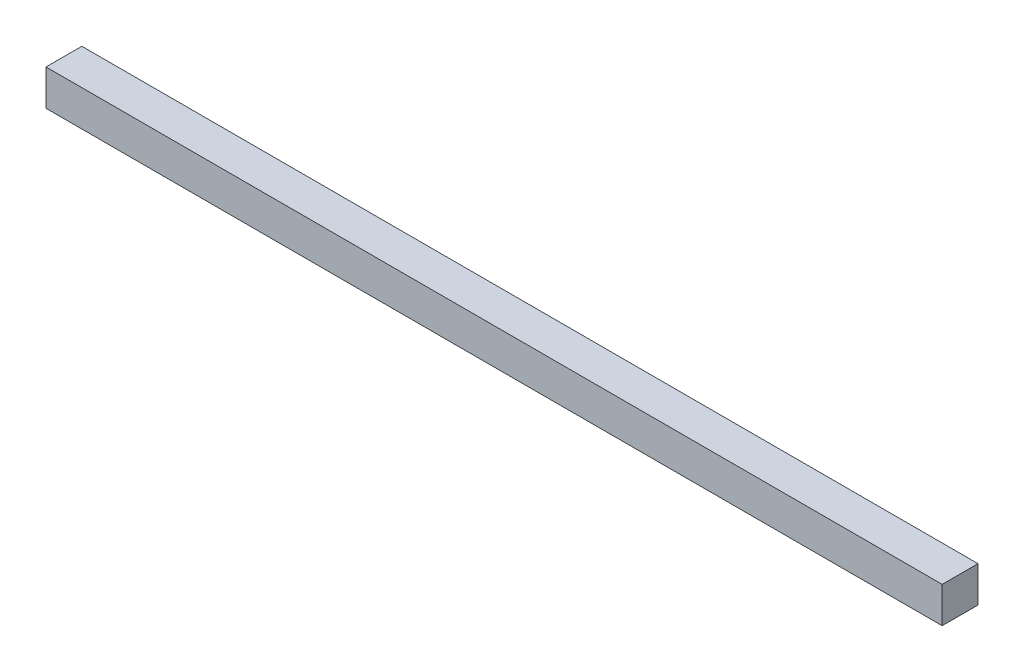
SolidWorks part; units mm, degrees
ref_plane "前视基准面" through (0, 0, 0) normal (0, 0, 1) x (1, 0, 0)
ref_plane "上视基准面" through (0, 0, 0) normal (0, 1, 0) x (1, 0, 0)
ref_plane "右视基准面" through (0, 0, 0) normal (1, 0, 0) x (0, 0, -1)
sketch "草图1" plane through (0, 0, 0) normal (0, 1, 0) x (1, 0, 0)
  line L1 (-600, -200) -> (-100, -200)
  line L2 (-600, -200) -> (-600, -220)
  line L3 (-600, -220) -> (-100, -220)
  line L4 (-100, -200) -> (-100, -220)
  line L5 (-600, -200) -> (-100, -220) construction
  line L6 (-600, -220) -> (-100, -200) construction
  point P0 (-350, -210)
  point P5 (0, 0)
  dimension "D1" = 500
  dimension "D2" = 20
  dimension "D3" = 200
extrude "凸台-拉伸1" add sketch "草图1" along normal blind 20
